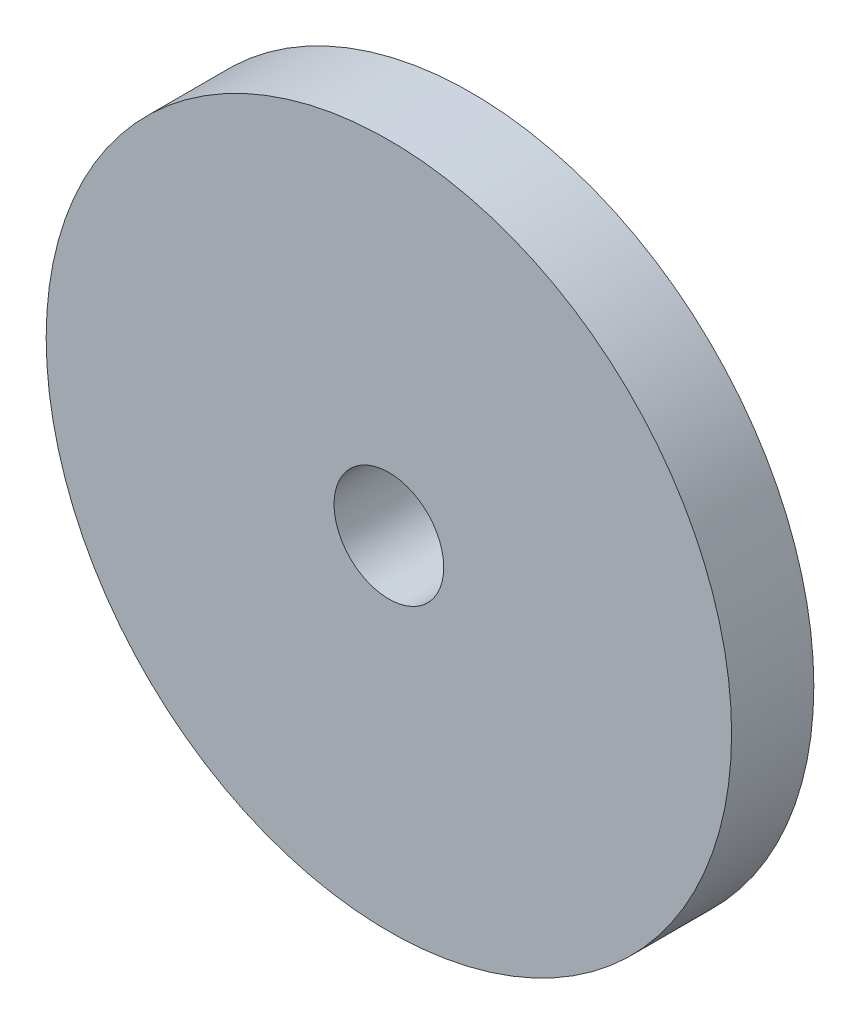
SolidWorks part; units mm, degrees
material "Oak"
ref_plane "Front Plane" through (0, 0, 0) normal (0, 0, 1) x (1, 0, 0)
ref_plane "Top Plane" through (0, 0, 0) normal (0, 1, 0) x (1, 0, 0)
ref_plane "Right Plane" through (0, 0, 0) normal (1, 0, 0) x (0, 0, -1)
sketch "Sketch1" plane through (0, 0, 0) normal (0, 0, 1) x (1, 0, 0)
  circle A0 centre (0, 0) radius 25
  dimension "D1" = 50
extrude "Boss-Extrude1" add sketch "Sketch1" along normal blind 6
sketch "Sketch2" plane through (0, 0, 6) normal (0, 0, 1) x (1, 0, 0)
  circle A0 centre (0, 0) radius 4
  dimension "D1" = 8
extrude "Cut-Extrude1" cut sketch "Sketch2" against normal through all
